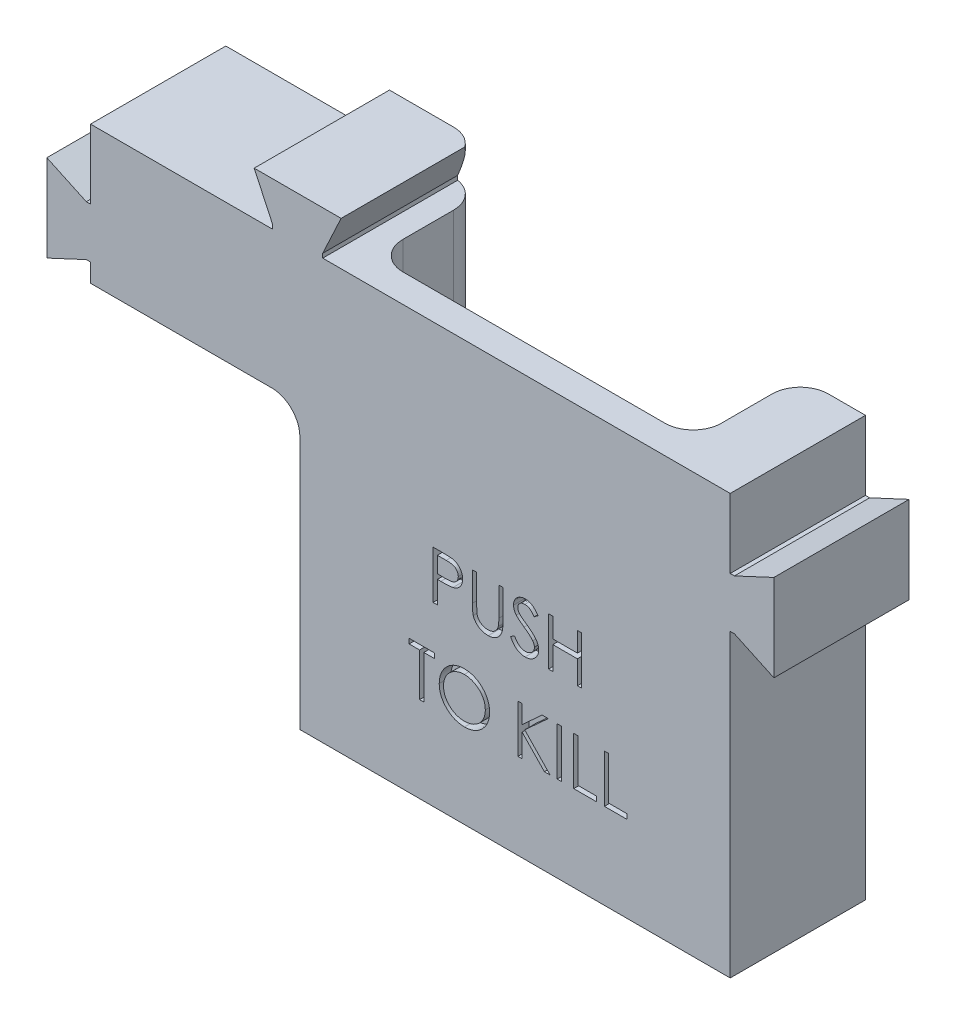
SolidWorks part; units mm, degrees
ref_plane "Front Plane" through (0, 0, 0) normal (0, 0, 1) x (1, 0, 0)
ref_plane "Top Plane" through (0, 0, 0) normal (0, 1, 0) x (1, 0, 0)
ref_plane "Right Plane" through (0, 0, 0) normal (1, 0, 0) x (0, 0, -1)
sketch "Sketch1" plane through (0, 0, 0) normal (0, 0, 1) x (1, 0, 0)
  line L6 (4.9264, 102.8422) -> (21.3356, 102.8422)
  line L7 (21.3356, 102.8422) -> (21.3356, 103.2232)
  line L8 (25.8551, 102.8422) -> (25.8551, 103.2232)
  line L9 (21.0554, 103.2232) -> (19.2787, 107.0332) construction
  line L10 (19.2787, 107.0332) -> (27.912, 107.0332) construction
  line L11 (27.912, 107.0332) -> (26.1354, 103.2232) construction
  line L12 (27.5133, 106.7792) -> (25.8551, 103.2232)
  line L13 (19.6774, 106.7792) -> (27.5133, 106.7792)
  line L14 (21.3356, 103.2232) -> (19.6774, 106.7792)
  line L19 (4.5454, 91.7932) -> (4.5454, 96.8732) construction
  line L20 (4.5454, 91.7932) -> (0.7354, 90.0165) construction
  line L21 (0.7354, 98.6498) -> (4.5454, 96.8732) construction
  line L22 (0.7354, 90.0165) -> (0.7354, 98.6498) construction
  line L23 (66.7754, 90.0165) -> (62.9654, 91.7932) construction
  line L24 (62.9654, 96.8732) -> (66.7754, 98.6498) construction
  line L25 (66.7754, 98.6498) -> (66.7754, 90.0165) construction
  line L26 (62.9654, 103.2232) -> (62.9654, 96.8732) construction
  line L27 (48.4239, 103.2232) -> (62.9654, 103.2232) construction
  line L39 (4.5454, 92.0734) -> (0.9894, 90.4152)
  line L40 (0.9894, 90.4152) -> (0.9894, 98.2511)
  line L41 (0.9894, 98.2511) -> (4.5454, 96.5929)
  line L57 (4.5454, 92.0734) -> (4.9264, 92.0734)
  line L58 (4.9264, 92.0734) -> (4.9264, 90.4152)
  line L59 (4.9264, 90.4152) -> (62.5844, 90.4152)
  line L63 (66.5214, 90.4152) -> (62.9654, 92.0734)
  line L64 (66.5214, 98.2511) -> (66.5214, 90.4152)
  line L65 (62.9654, 96.5929) -> (66.5214, 98.2511)
  line L66 (62.5844, 90.4152) -> (62.5844, 92.0734)
  line L67 (62.5844, 92.0734) -> (62.9654, 92.0734)
  line L68 (4.5454, 96.5929) -> (4.9264, 96.5929)
  line L69 (4.9264, 96.5929) -> (4.9264, 102.8422)
  line L71 (62.5844, 102.8422) -> (62.5844, 96.5929)
  line L72 (62.5844, 96.5929) -> (62.9654, 96.5929)
  line L76 (25.8551, 102.8422) -> (62.5844, 102.8422)
  point P8 (3.81, 87.2124)
  point P14 (0.381, 85.7358)
  point P34 (62.391, 87.2872)
  point P35 (65.8118, 85.9562)
  point P42 (61.7814, 91.7519)
  point P43 (62.1624, 91.4873)
  point P48 (20.2212, 97.79)
  point P50 (20.5284, 98.325)
  dimension "D4" = 0.381
  dimension "D5" = 0.254
  dimension "D1" = 0.254
  dimension "D3" = 0.254
  dimension "D2" = 0.254
  dimension "D6" = 0.254
  dimension "D7" = 0.254
  dimension "D8" = 0.254
  dimension "D9" = 0.254
  dimension "D10" = 0.254
  dimension "D11" = 0.381
  dimension "D12" = 0.381
extrude "Boss-Extrude1" add sketch "Sketch1" along normal blind 12.192
sketch "Sketch2" plane through (0, 90.4152, 0) normal (0, -1, 0) x (1, 0, 0)
  line L0 (4.9264, 0) -> (62.5844, 0) construction
  line L1 (28.0035, 0) -> (56.7055, 0)
  line L2 (28.0035, 0) -> (28.0035, 9.652)
  line L3 (28.0035, 9.652) -> (56.7055, 9.652)
  line L4 (56.7055, 0) -> (56.7055, 9.652)
  line L7 (31.8135, -0.9884) -> (31.8135, -13.1804) construction
  line L8 (52.8955, -0.9884) -> (52.8955, -13.1804) construction
  line L9 (4.9264, 12.192) -> (62.5844, 12.192) construction
  dimension "D1" = 3.81
  dimension "D2" = 3.81
  dimension "D3" = 2.54
extrude "Cut-Extrude1" cut sketch "Sketch2" against normal through all
fillet "Fillet1" radius 2.54 4 edges at (56.7055, 96.6287, 0) (28.0035, 96.6287, 0) (28.0035, 96.6287, 9.652) (56.7055, 96.6287, 9.652)
sketch "Sketch3" plane through (0, 90.4152, 0) normal (0, -1, 0) x (1, 0, 0)
  line L0 (4.9264, 0) -> (25.4635, 0) construction
  line L1 (23.7939, 0) -> (62.5844, 0)
  line L2 (23.7939, 0) -> (23.7939, 12.192)
  line L3 (23.7939, 12.192) -> (62.5844, 12.192)
  line L4 (62.5844, 0) -> (62.5844, 12.192)
  line L20 (56.7055, 7.112) -> (56.7055, 2.54)
  line L21 (30.5435, 9.652) -> (54.1655, 9.652)
  line L22 (28.0035, 2.54) -> (28.0035, 7.112)
  line L23 (56.7055, 7.112) -> (56.7055, 2.54)
  line L24 (30.5435, 9.652) -> (54.1655, 9.652)
  line L25 (28.0035, 2.54) -> (28.0035, 7.112)
  arc A20 (56.7055, 2.54) -> (59.2455, 0) centre (59.2455, 2.54) ccw
  arc A21 (56.7055, 7.112) -> (54.1655, 9.652) centre (54.1655, 7.112) ccw
  arc A22 (30.5435, 9.652) -> (28.0035, 7.112) centre (30.5435, 7.112) ccw
  arc A23 (25.4635, 0) -> (28.0035, 2.54) centre (25.4635, 2.54) ccw
  arc A24 (56.7055, 2.54) -> (59.2455, 0) centre (59.2455, 2.54) ccw
  arc A25 (56.7055, 7.112) -> (54.1655, 9.652) centre (54.1655, 7.112) ccw
  arc A26 (30.5435, 9.652) -> (28.0035, 7.112) centre (30.5435, 7.112) ccw
  arc A27 (25.4635, 0) -> (28.0035, 2.54) centre (25.4635, 2.54) ccw
  line M12 (56.7055, 7.112) -> (56.7055, 2.54)
  arc M13 (56.7055, 2.54) -> (59.2455, 0) centre (59.2455, 2.54) ccw
  line M14 (59.2455, 0) -> (62.5844, 0)
  line M15 (62.5844, 0) -> (62.5844, 12.192)
  line M16 (62.5844, 12.192) -> (4.9264, 12.192)
  line M18 (4.9264, 0) -> (25.4635, 0)
  arc M19 (25.4635, 0) -> (28.0035, 2.54) centre (25.4635, 2.54) ccw
  line M20 (28.0035, 2.54) -> (28.0035, 7.112)
  arc M21 (28.0035, 7.112) -> (30.5435, 9.652) centre (30.5435, 7.112) cw
  line M22 (30.5435, 9.652) -> (54.1655, 9.652)
  arc M23 (54.1655, 9.652) -> (56.7055, 7.112) centre (54.1655, 7.112) cw
  dimension "D1" = 0
extrude "Boss-Extrude2" add sketch "Sketch3" along normal blind 25.4 contours L2 M18 M19 M20 M21 M22 M23 M12 M13 M14 M15 M16
fillet "Fillet2" radius 2.54 1 edges at (23.7939, 90.4152, 6.096)
sketch "Sketch4" plane through (0, 0, 12.192) normal (0, 0, 1) x (1, 0, 0)
  text T0 " PUSH\r\nTO KILL" font "Century Gothic" height 4.318
extrude "Cut-Extrude2" cut sketch "Sketch4" against normal blind 1.016
